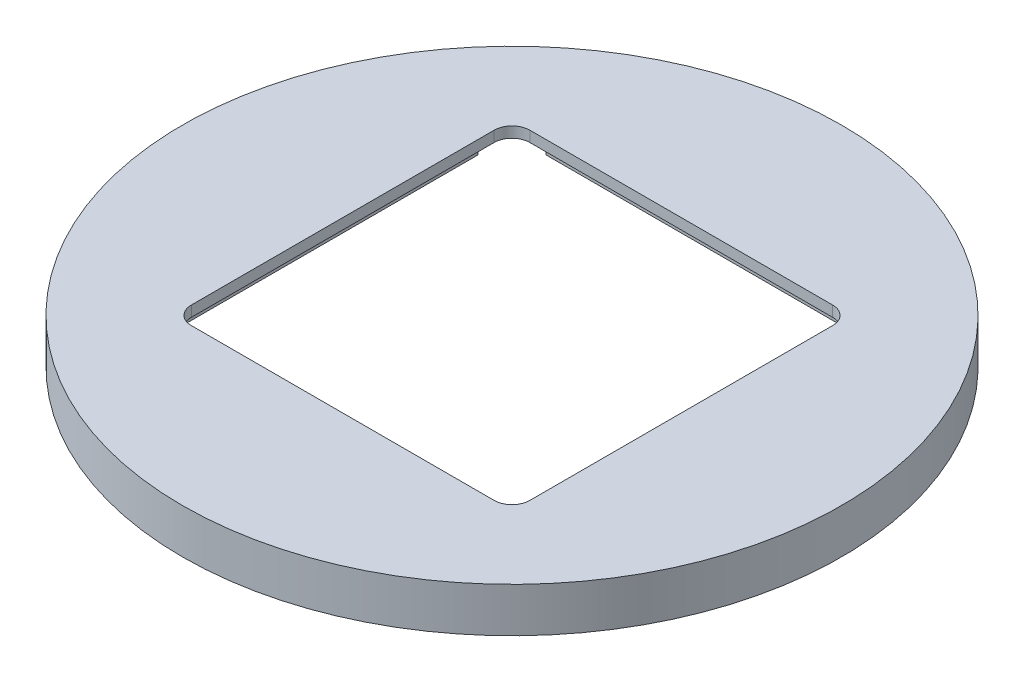
SolidWorks part; units mm, degrees
material "ABS"
ref_plane "Front Plane" through (0, 0, 0) normal (0, 0, 1) x (1, 0, 0)
ref_plane "Top Plane" through (0, 0, 0) normal (0, 1, 0) x (1, 0, 0)
ref_plane "Right Plane" through (0, 0, 0) normal (1, 0, 0) x (0, 0, -1)
sketch "Sketch2" plane through (0, 0, 0) normal (0, 1, 0) x (1, 0, 0)
  line L1 (-10.1337, 10.6287) -> (-32.6337, 10.6287)
  line L2 (-10.1337, 10.6287) -> (-10.1337, -11.8713)
  line L3 (-10.1337, -11.8713) -> (-32.6337, -11.8713)
  line L4 (-32.6337, 10.6287) -> (-32.6337, -11.8713)
  line L5 (-10.1337, 10.6287) -> (-32.6337, -11.8713) construction
  line L6 (-10.1337, -11.8713) -> (-32.6337, 10.6287) construction
  circle A0 centre (-21.3837, -0.6213) radius 18.5
  dimension "D1" = 22.5
  dimension "D2" = 37
  dimension "D3" = 21.3837
  dimension "D4" = 22.5
extrude "Boss-Extrude1" add sketch "Sketch2" along normal blind 2.5
sketch "Sketch4" plane through (0, 0, 0) normal (0, -1, 0) x (1, 0, 0)
  circle A0 centre (-21.5697, 16.4013) radius 1.67
  circle A1 centre (-21.3837, 0.6213) radius 18.5 construction
  point P2 (0, 0)
  dimension "D1" = 3.34
  dimension "D2" = 15.78
extrude "Cut-Extrude1" cut sketch "Sketch4" against normal blind 1.15
pattern_circular "CirPattern1" count 4 over 360 about axis through (-21.3837, 0, 0.6213) along (0, 1, 0) of "Cut-Extrude1"
sketch "Sketch5" plane through (0, 2.5, 0) normal (0, 1, 0) x (1, 0, 0)
  line L1 (-11.8837, 8.8787) -> (-30.8837, 8.8787)
  line L2 (-11.8837, 8.8787) -> (-11.8837, -10.1213)
  line L3 (-11.8837, -10.1213) -> (-30.8837, -10.1213)
  line L4 (-30.8837, 8.8787) -> (-30.8837, -10.1213)
  line L5 (-11.8837, 8.8787) -> (-30.8837, -10.1213) construction
  line L6 (-11.8837, -10.1213) -> (-30.8837, 8.8787) construction
  point P0 (-21.3837, -0.6213)
  line M1 (-32.6337, -11.8713) -> (-32.6337, 10.6287)
  line M2 (-32.6337, 10.6287) -> (-10.1337, 10.6287)
  line M3 (-10.1337, 10.6287) -> (-10.1337, -11.8713)
  line M4 (-10.1337, -11.8713) -> (-32.6337, -11.8713)
  dimension "D1" = 19
  dimension "D2" = 19
extrude "Boss-Extrude2" add sketch "Sketch5" against normal blind 0.6 contours L4 L1 L2 L3 M1 M4 M3 M2
fillet "Fillet1" radius 1 4 edges at (-30.8837, 2.2, 10.1213) (-11.8837, 2.2, 10.1213) (-11.8837, 2.2, -8.8787) (-30.8837, 2.2, -8.8787)
sketch "Sketch6" plane through (0, 0, 0) normal (0, -1, 0) x (-1, 0, 0)
  line L0 (32.6337, -11.8713) -> (32.1337, -11.3713) construction
  line L1 (32.6337, -11.8713) -> (32.1337, -11.8713) construction
  line L2 (10.1337, -11.8713) -> (32.6337, -11.8713) construction
  line L3 (32.1337, -11.8713) -> (32.1337, -11.3713) construction
  line L4 (10.1337, -11.8713) -> (10.6337, -11.3713) construction
  line L5 (10.1337, -11.8713) -> (10.1337, -11.3713) construction
  line L6 (10.1337, -11.3713) -> (10.6337, -11.3713) construction
  line L7 (10.1337, 10.6287) -> (10.6337, 10.1287) construction
  line L8 (10.1337, 10.6287) -> (10.6337, 10.6287) construction
  line L9 (10.6337, 10.6287) -> (10.6337, 10.1287) construction
  line L10 (32.6337, 10.6287) -> (32.1337, 10.1287) construction
  line L11 (32.6337, 10.6287) -> (32.6337, 10.1287) construction
  line L12 (32.6337, 10.1287) -> (32.1337, 10.1287) construction
  line L13 (10.1337, -0.6213) -> (32.6337, -0.6213) construction
  line L14 (10.1337, 10.6287) -> (10.1337, -11.8713) construction
  line L15 (32.6337, 10.6287) -> (32.6337, -11.8713) construction
  line L16 (21.3837, -11.8713) -> (21.3837, 10.6287) construction
  line L17 (10.1337, 10.6287) -> (32.6337, 10.6287) construction
  circle A0 centre (32.1337, -11.3713) radius 1.5
  circle A1 centre (10.6337, -11.3713) radius 1.5
  circle A2 centre (10.6337, 10.1287) radius 1.5
  circle A3 centre (32.1337, 10.1287) radius 1.5
  circle A4 centre (21.3837, -0.6213) radius 1.1377 construction
  point P22 (21.3837, -0.6213)
  dimension "D3" = 3
  dimension "D1" = 0.5
  dimension "D2" = 0.5
  dimension "D4" = 4
extrude "Cut-Extrude2" cut sketch "Sketch6" against normal up to surface (1.9 mm away) up to face at (-21.3837, 1.9, 0.6213)
